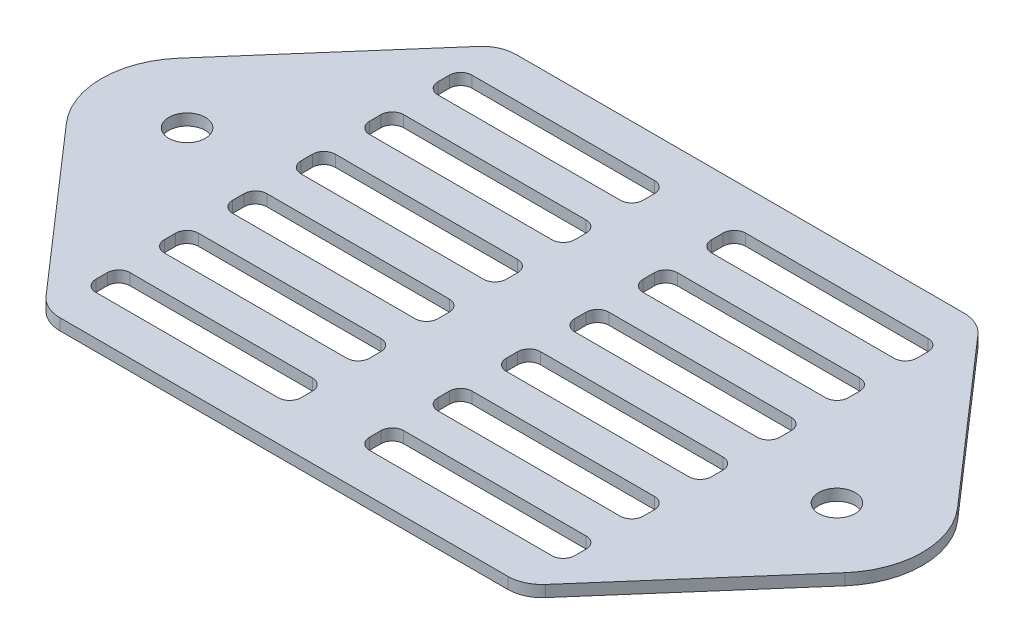
SolidWorks part; units mm, degrees
material "碳板"
ref_plane "前视基准面" through (0, 0, 0) normal (0, 0, 1) x (1, 0, 0)
ref_plane "上视基准面" through (0, 0, 0) normal (0, 1, 0) x (1, 0, 0)
ref_plane "右视基准面" through (0, 0, 0) normal (1, 0, 0) x (0, 0, -1)
sketch "草图1" plane through (0, 0, 0) normal (0, 1, 0) x (1, 0, 0)
  line L0 (-59.2941, 0) -> (65.4706, 0) construction
  line L1 (-36, 20) -> (36, 20)
  line L2 (-36, 20) -> (-36, -20)
  line L3 (-36, -20) -> (36, -20)
  line L4 (36, 20) -> (36, -20)
  line L5 (-36, 20) -> (36, -20) construction
  line L6 (-36, -20) -> (36, 20) construction
  line L7 (0, 49.1471) -> (0, -45.9706) construction
  line L8 (3, -13.5) -> (3, -16.5)
  line L9 (-21, -13.5) -> (-3, -13.5)
  line L10 (-21, -13.5) -> (-21, -16.5)
  line L11 (-21, -16.5) -> (-3, -16.5)
  line L12 (-3, -13.5) -> (-3, -16.5)
  line L13 (-21, -13.5) -> (-3, -16.5) construction
  line L14 (-21, -16.5) -> (-3, -13.5) construction
  line L15 (3, -13.5) -> (21, -13.5)
  line L16 (21, -13.5) -> (21, -16.5)
  line L17 (3, -16.5) -> (21, -16.5)
  line L18 (3, -7.5) -> (3, -10.5)
  line L19 (3, -7.5) -> (21, -7.5)
  line L20 (21, -7.5) -> (21, -10.5)
  line L21 (3, -10.5) -> (21, -10.5)
  line L22 (3, -1.5) -> (3, -4.5)
  line L23 (3, -1.5) -> (21, -1.5)
  line L24 (21, -1.5) -> (21, -4.5)
  line L25 (3, -4.5) -> (21, -4.5)
  line L26 (3, 4.5) -> (3, 1.5)
  line L27 (3, 4.5) -> (21, 4.5)
  line L28 (21, 4.5) -> (21, 1.5)
  line L29 (3, 1.5) -> (21, 1.5)
  line L30 (3, 10.5) -> (3, 7.5)
  line L31 (3, 10.5) -> (21, 10.5)
  line L32 (21, 10.5) -> (21, 7.5)
  line L33 (3, 7.5) -> (21, 7.5)
  line L34 (3, 16.5) -> (3, 13.5)
  line L35 (3, 16.5) -> (21, 16.5)
  line L36 (21, 16.5) -> (21, 13.5)
  line L37 (3, 13.5) -> (21, 13.5)
  line L38 (-21, -7.5) -> (-21, -10.5)
  line L39 (-21, -7.5) -> (-3, -7.5)
  line L40 (-3, -7.5) -> (-3, -10.5)
  line L41 (-21, -10.5) -> (-3, -10.5)
  line L42 (-21, -1.5) -> (-21, -4.5)
  line L43 (-21, -1.5) -> (-3, -1.5)
  line L44 (-3, -1.5) -> (-3, -4.5)
  line L45 (-21, -4.5) -> (-3, -4.5)
  line L46 (-21, 4.5) -> (-21, 1.5)
  line L47 (-21, 4.5) -> (-3, 4.5)
  line L48 (-3, 4.5) -> (-3, 1.5)
  line L49 (-21, 1.5) -> (-3, 1.5)
  line L50 (-21, 10.5) -> (-21, 7.5)
  line L51 (-21, 10.5) -> (-3, 10.5)
  line L52 (-3, 10.5) -> (-3, 7.5)
  line L53 (-21, 7.5) -> (-3, 7.5)
  line L54 (-21, 16.5) -> (-21, 13.5)
  line L55 (-21, 16.5) -> (-3, 16.5)
  line L56 (-3, 16.5) -> (-3, 13.5)
  line L57 (-21, 13.5) -> (-3, 13.5)
  line L58 (-21, 20) -> (-34.1507, 4.9315)
  line L59 (21, 20) -> (34.1507, 4.9315)
  line L60 (21, -20) -> (34.1507, -4.9315)
  line L61 (-21, -20) -> (-34.1507, -4.9315)
  circle A0 centre (-28.5, 0) radius 1.6
  circle A1 centre (28.5, 0) radius 1.6
  circle A2 centre (-28.5, 0) radius 7.5
  circle A3 centre (28.5, 0) radius 7.5
  point P0 (0, 0)
  point P14 (-12, -15)
  dimension "D3" = 3.2
  dimension "D11" = 15
  dimension "D1" = 72
  dimension "D2" = 40
  dimension "D4" = 7.5
  dimension "D5" = 3
  dimension "D6" = 18
  dimension "D7" = 15
  dimension "D10" = 6
  dimension "D8" = 2
  dimension "D9" = 6
extrude "凸台-拉伸1" add sketch "草图1" along normal blind 1 contours L60 A3 L59 L1 L58 A2 L61 L3 L57 L54 L55 L56 L53 L50 L51 L52 L49 L46 L47 L48 L45 L42 L43 L44 L41 L38 L39 L40 L37 L34 L35 L36 L33 L30 L31 L32 L29 L26 L27 L28 L25 L22 | A2 A0 | A3 A1
fillet "圆角1" radius 3 4 edges at (21, 0.5, 20) (21, 0.5, -20) (-21, 0.5, 20) (-21, 0.5, -20)
fillet "圆角2" radius 1 48 edges at (-21, 0.5, 13.5) (-21, 0.5, 16.5) (-3, 0.5, 16.5) (-3, 0.5, 13.5) (21, 0.5, 16.5) (21, 0.5, 13.5) (3, 0.5, 13.5) (3, 0.5, 16.5) (21, 0.5, 10.5) (21, 0.5, 7.5) (3, 0.5, 7.5) (3, 0.5, 10.5) (21, 0.5, 4.5) (21, 0.5, 1.5) (3, 0.5, 1.5) (3, 0.5, 4.5) (21, 0.5, -1.5) (21, 0.5, -4.5) (3, 0.5, -4.5) (3, 0.5, -1.5) (21, 0.5, -7.5) (21, 0.5, -10.5) (3, 0.5, -10.5) (3, 0.5, -7.5) (21, 0.5, -13.5) (21, 0.5, -16.5) (3, 0.5, -16.5) (3, 0.5, -13.5) (-3, 0.5, 10.5) (-3, 0.5, 7.5) (-21, 0.5, 7.5) (-21, 0.5, 10.5) (-3, 0.5, 4.5) (-3, 0.5, 1.5) (-21, 0.5, 1.5) (-21, 0.5, 4.5) (-3, 0.5, -1.5) (-3, 0.5, -4.5) (-21, 0.5, -4.5) (-21, 0.5, -1.5) (-3, 0.5, -7.5) (-3, 0.5, -10.5) (-21, 0.5, -10.5) (-21, 0.5, -7.5) (-3, 0.5, -13.5) (-3, 0.5, -16.5) (-21, 0.5, -13.5) (-21, 0.5, -16.5)
